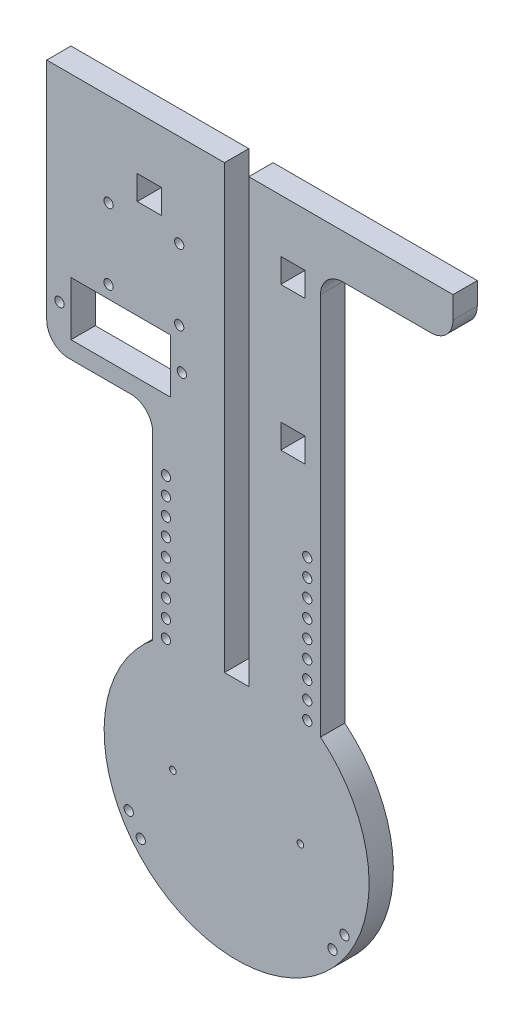
SolidWorks part; units mm, degrees
material "ﾁｰｸ材"
ref_plane "正面" through (0, 0, 0) normal (0, 0, 1) x (1, 0, 0)
ref_plane "平面" through (0, 0, 0) normal (0, 1, 0) x (1, 0, 0)
ref_plane "右側面" through (0, 0, 0) normal (1, 0, 0) x (0, 0, -1)
sketch "ｽｹｯﾁ1" plane through (0, 0, 0) normal (0, 0, 1) x (1, 0, 0)
  line L0 (19, 125) -> (-43, 125)
  line L2 (19, 115) -> (19, 23.2164)
  line L7 (-43, 69) -> (-43, 125)
  line L11 (-19, 69) -> (-19, 23.2164)
  line L12 (-19, 69) -> (-43, 69)
  line L13 (19, 115) -> (49, 115)
  line L14 (49, 115) -> (49, 125)
  line L15 (49, 125) -> (19, 125)
  arc A0 (-19, 23.2164) -> (19, 23.2164) centre (0, 0) ccw
  dimension "D1" = 60
  dimension "D7" = 30
  dimension "D2" = 125
  dimension "D3" = 19
  dimension "D4" = 56
  dimension "D5" = 43
  dimension "D6" = 10
extrude "ﾎﾞｽ - 押し出し1" add sketch "ｽｹｯﾁ1" along normal blind 5.5
sketch "ｽｹｯﾁ3" plane through (0, 0, 5.5) normal (0, 0, 1) x (1, 0, 0)
  line L0 (0, 0) -> (0, 22.4882) construction
sketch "ｽｹｯﾁ5" plane through (0, 0, 5.5) normal (0, 0, 1) x (1, 0, 0)
  circle A0 centre (14.45, 0) radius 0.75
  circle A1 centre (-14.45, 0) radius 0.75
  dimension "D1" = 14.45
  dimension "D2" = 1.5
  dimension "D3" = 14.45
extrude "ｶｯﾄ - 押し出し3" cut sketch "ｽｹｯﾁ5" against normal through all
sketch "ｽｹｯﾁ6" plane through (0, 0, 5.5) normal (0, 0, 1) x (1, 0, 0)
  line L0 (0, 0) -> (-25.1601, -16.3392) construction
  line L1 (0, 0) -> (0, 22.4882) construction
  line L2 (-21.7018, -17.0742) -> (-24.425, -12.8809) construction
  line L3 (0, 0) -> (0, -5.9449) construction
  arc A0 (-19, 23.2164) -> (19, 23.2164) centre (0, 0) ccw construction
  circle A1 centre (-24.425, -12.8809) radius 1.05
  circle A2 centre (-21.7018, -17.0742) radius 1.05
  circle A3 centre (24.425, -12.8809) radius 1.05
  circle A4 centre (21.7018, -17.0742) radius 1.05
  point P12 (-23.0634, -14.9776)
  dimension "D2" = 5
  dimension "D3" = 2.1
  dimension "D4" = 2.1
  dimension "D1" = 123
  dimension "D5" = 27.5
extrude "ｶｯﾄ - 押し出し4" cut sketch "ｽｹｯﾁ6" against normal through all
sketch "ｽｹｯﾁ8" plane through (0, 0, 5.5) normal (0, 0, 1) x (1, 0, 0)
  line L0 (0, 0) -> (0, 22.4882) construction
  line L1 (15.5, 107.5) -> (10, 107.5)
  line L2 (15.5, 107.5) -> (15.5, 113)
  line L3 (15.5, 113) -> (10, 113)
  line L4 (10, 107.5) -> (10, 113)
  line L5 (-22.5, 113) -> (-17, 113)
  line L6 (-22.5, 113) -> (-22.5, 107.5)
  line L7 (-22.5, 107.5) -> (-17, 107.5)
  line L8 (-17, 113) -> (-17, 107.5)
  line L9 (49, 125) -> (-43, 125) construction
  line L10 (15.5, 75) -> (10, 75)
  line L11 (15.5, 75) -> (15.5, 80.5)
  line L12 (15.5, 80.5) -> (10, 80.5)
  line L13 (10, 75) -> (10, 80.5)
  point P10 (-17, 110.25)
  dimension "D1" = 5.5
  dimension "D2" = 10
  dimension "D3" = 17
  dimension "D4" = 12
  dimension "D5" = 27
extrude "ｶｯﾄ - 押し出し6" cut sketch "ｽｹｯﾁ8" against normal through all
sketch "ｽｹｯﾁ9" plane through (0, 0, 5.5) normal (0, 0, 1) x (1, 0, 0)
  line L0 (0, 0) -> (0, 22.4882) construction
  line L1 (0, 0) -> (0, 13.9203) construction
  circle A0 centre (16, 25) radius 1.05
  circle A1 centre (16, 29) radius 1.05
  circle A2 centre (16, 33) radius 1.05
  circle A3 centre (16, 37) radius 1.05
  circle A4 centre (16, 41) radius 1.05
  circle A5 centre (16, 45) radius 1.05
  circle A6 centre (16, 49) radius 1.05
  circle A7 centre (16, 53) radius 1.05
  circle A8 centre (16, 57) radius 1.05
  circle A9 centre (-16, 57) radius 1.05
  circle A10 centre (-16, 53) radius 1.05
  circle A11 centre (-16, 49) radius 1.05
  circle A12 centre (-16, 45) radius 1.05
  circle A13 centre (-16, 41) radius 1.05
  circle A14 centre (-16, 37) radius 1.05
  circle A15 centre (-16, 33) radius 1.05
  circle A16 centre (-16, 29) radius 1.05
  circle A17 centre (-16, 25) radius 1.05
  dimension "D1" = 2.1
  dimension "D2" = 16
  dimension "D4" = 25
  dimension "D3" = 9
extrude "ｶｯﾄ - 押し出し7" cut sketch "ｽｹｯﾁ9" against normal through all
sketch "ｽｹｯﾁ10" plane through (0, 0, 5.5) normal (0, 0, 1) x (1, 0, 0)
  line L0 (49, 125) -> (-43, 125) construction
  line L1 (2.75, 25) -> (-2.75, 25)
  line L2 (2.75, 25) -> (2.75, 125)
  line L3 (2.75, 125) -> (-2.75, 125)
  line L4 (-2.75, 25) -> (-2.75, 125)
  line L5 (2.75, 25) -> (-2.75, 125) construction
  line L6 (2.75, 125) -> (-2.75, 25) construction
  point P0 (0, 75)
  dimension "D1" = 5.5
  dimension "D2" = 25
extrude "ｶｯﾄ - 押し出し8" cut sketch "ｽｹｯﾁ10" against normal through all
sketch "ｽｹｯﾁ11" plane through (0, 0, 5.5) normal (0, 0, 1) x (1, 0, 0)
  line L0 (-2.75, 125) -> (-43, 125) construction
  line L1 (0, 0) -> (0, 22.4882) construction
  circle A0 centre (-13, 104) radius 1.05
  circle A1 centre (-29, 104) radius 1.05
  circle A2 centre (-13, 88) radius 1.05
  circle A3 centre (-29, 88) radius 1.05
  dimension "D1" = 2.1
  dimension "D2" = 21
  dimension "D3" = 16
  dimension "D4" = 13
  dimension "D5" = 16
extrude "ｶｯﾄ - 押し出し9" cut sketch "ｽｹｯﾁ11" against normal through all
sketch "ｽｹｯﾁ12" plane through (0, 0, 5.5) normal (0, 0, 1) x (1, 0, 0)
  line L1 (-15, 72.9) -> (-37.5, 72.9)
  line L2 (-15, 72.9) -> (-15, 85.1)
  line L3 (-15, 85.1) -> (-37.5, 85.1)
  line L4 (-37.5, 72.9) -> (-37.5, 85.1)
  line L5 (-15, 72.9) -> (-37.5, 85.1) construction
  line L6 (-15, 85.1) -> (-37.5, 72.9) construction
  line L7 (0, 0) -> (0, 22.4882) construction
  line L8 (-2.75, 125) -> (-43, 125) construction
  circle A0 centre (-40.1, 79) radius 1.05
  circle A1 centre (-12.4, 79) radius 1.05
  point P0 (-26.25, 79)
  dimension "D5" = 2.1
  dimension "D1" = 12.2
  dimension "D2" = 22.5
  dimension "D3" = 15
  dimension "D4" = 46
  dimension "D6" = 2.6
  dimension "D7" = 2.6
extrude "ｶｯﾄ - 押し出し10" cut sketch "ｽｹｯﾁ12" against normal blind 10
fillet "ﾌｨﾚｯﾄ1" radius 5 2 edges at (-43, 69, 2.75) (-19, 69, 2.75)
fillet "ﾌｨﾚｯﾄ2" radius 5 2 edges at (49, 115, 2.75) (19, 115, 2.75)
